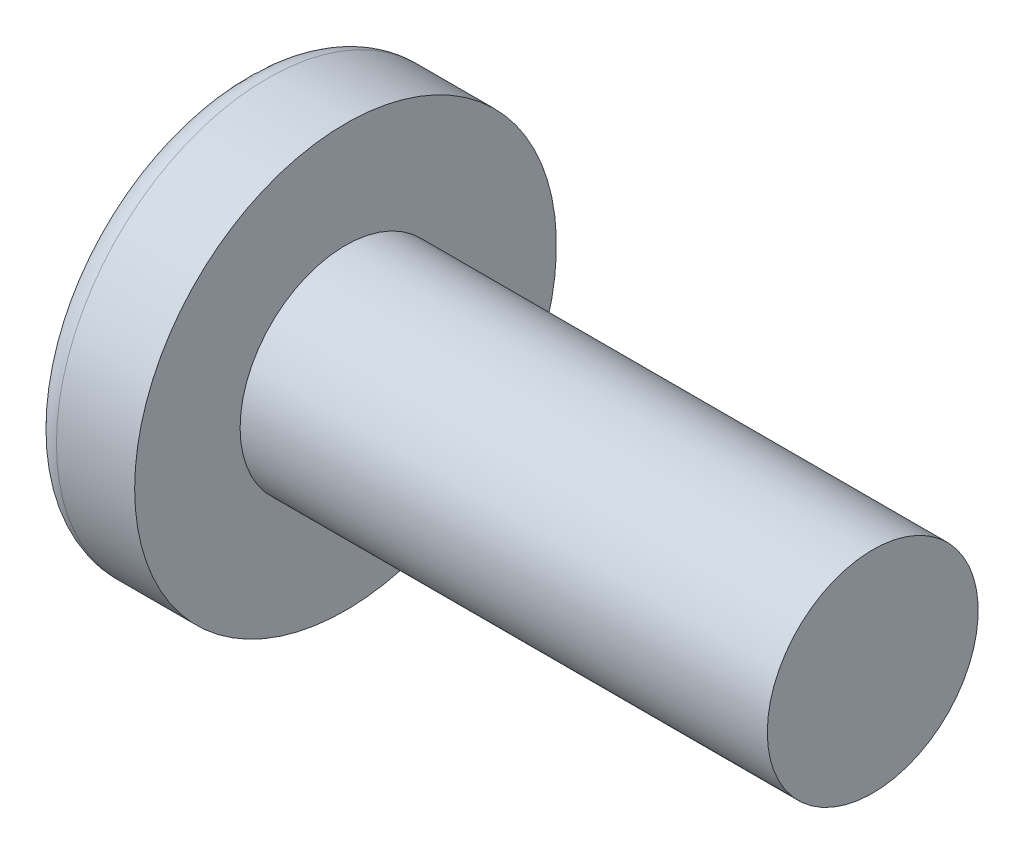
SolidWorks part; units mm, degrees
ref_plane "Plane1" through (0, 0, 0) normal (0, 0, 1) x (1, 0, 0)
ref_plane "Plane2" through (0, 0, 0) normal (0, 1, 0) x (1, 0, 0)
ref_plane "Plane3" through (0, 0, 0) normal (1, 0, 0) x (0, 0, -1)
sketch "BodySke" plane through (0, 0, 0) normal (0, 0, 1) x (1, 0, 0)
  line L0 (3.1, 2) -> (3.1, 4)
  line L1 (3.8, 6.35) -> (3.8, -3.175) construction
  line L2 (-25.4, 0) -> (127, 0) construction
  line L3 (13.1, 0) -> (0, 0)
  line L4 (3.1, 2) -> (13.1, 2)
  line L5 (13.1, 2) -> (13.1, 0)
  line L6 (1.6164, 4) -> (3.1, 4)
  line L7 (3.1, -2) -> (13.1, -2) construction
  line L8 (3.1, 6.35) -> (3.1, -3.175) construction
  arc A0 (1.227, 3.8007) -> (0, 0) centre (6.5, 0) ccw
  arc A2 (1.227, 3.8007) -> (1.6164, 4) centre (1.6164, 3.52) cw
  dimension "Head_fillet_rad" = 0.48
  dimension "Head_crown_rad" = 6.5
  dimension "Head_ht" = 3.1
  dimension "Diameter" = 4
  dimension "Length" = 10
  dimension "Head_dia" = 8
  dimension "Advance" = 0.7
  dimension "Thread_nom" = 10
revolve "Base-Revolve" add sketch "BodySke" angle 360 about L2
cosmetic thread "ThreadCosmetic" parameters "Thread_length"=9.3, "Thread_minor"=3.22
sketch "Sketch3" plane through (0, 0, 0) normal (1, 0, 0) x (0, 0, -1)
  line L0 (0.465, -2.2) -> (-0.465, -2.2)
  line L1 (0.465, -2.2) -> (0.465, 2.2)
  line L2 (-0.465, 2.2) -> (0.465, 2.2)
  line L3 (-0.465, 2.2) -> (-0.465, -2.2)
  dimension "D1" = 2.2
  dimension "Cross_dia" = 4.4
  dimension "D2" = 0.465
  dimension "Cross_width" = 0.93
ref_plane "Plane4" through (2.45, 0, 0) normal (1, 0, 0) x (0, 0, -1)
sketch "Sketch4" plane through (2.45, 0, 0) normal (1, 0, 0) x (0, 0, -1)
  line L0 (0.2325, -0.2325) -> (-0.2325, -0.2325)
  line L1 (0.2325, -0.2325) -> (0.2325, 0.2325)
  line L2 (-0.2325, 0.2325) -> (0.2325, 0.2325)
  line L3 (-0.2325, 0.2325) -> (-0.2325, -0.2325)
  dimension "D1" = 0.465
  dimension "D2" = 0.465
  dimension "D3" = 0.2325
  dimension "D4" = 0.2325
loft "Cut-Loft1" cut profiles "Sketch3", "Sketch4"
pattern_circular "CirPattern1" count 2 every 90 about axis through (0, 0, 0) along (1, 0, 0) of "Cut-Loft1"
sketch "ThdSchSke" plane through (0, 0, 0) normal (0, 0, 1) x (1, 0, 0)
  line L0 (3.8, -1.61) -> (3.5269, -2)
  line L1 (3.8, -1.61) -> (4.0731, -2)
  line L2 (4.0731, -2) -> (4.0731, -2.5)
  line L3 (-3.175, 0) -> (5.1513, 0) construction
  line L5 (4.0731, -2.5) -> (3.5269, -2.5)
  line L6 (3.5269, -2.5) -> (3.5269, -2)
  dimension "Thread_minor" = 3.22
  dimension "Diameter" = 4
  dimension "Start" = 3.8
  dimension "SideAngle" = 55
  dimension "VeeAngle" = 70
  dimension "Overcut" = 5
revolve "ThreadSchematic" [suppressed] cut sketch "ThdSchSke" angle 360 about L3
pattern_linear "ThdSchPat" [suppressed]
equation "\"D1@Sketch3\" = \"Cross_dia@Sketch3\" / 2"
equation "\"D2@Sketch3\" = \"Cross_width@Sketch3\" / 2"
equation "\"D1@Sketch4\" = \"Cross_width@Sketch3\" *.5"
equation "\"D2@Sketch4\" = \"D1@Sketch4\""
equation "\"D3@Sketch4\" = \"D1@Sketch4\" / 2"
equation "\"D4@Sketch4\" = \"D2@Sketch4\" / 2"
equation "\"Thread_length@ThreadCosmetic\" = ((sgn( (\"Length@BodySke\" - \"Advance@BodySke\" ) - \"Thread_nom@BodySke\" )-1)*( (\"Length@BodySke\" - \"Advance@BodySke\" ) - \"Thread_nom@BodySke\" ))/-2+ \"Thread_nom@BodySke\""
equation "\"Thread_minor@ThdSchSke\" = \"Thread_minor@ThreadCosmetic\""
equation "\"Diameter@ThdSchSke\" = \"Diameter@BodySke\""
equation "\"Overcut@ThdSchSke\" = \"Diameter@BodySke\" * 1.25"
equation "\"Start@ThdSchSke\" = \"Head_ht@BodySke\" + \"Length@BodySke\" - \"Thread_length@ThreadCosmetic\"  '---Non-countersunk---"
equation "\"Num_threads@ThdSchPat\" = int( \"Thread_length@ThreadCosmetic\" / \"Advance@BodySke\" + 0.999 )  + 1"
equation "\"Advance@ThdSchPat\" = \"Thread_length@ThreadCosmetic\" /  (\"Num_threads@ThdSchPat\" - 1) 'relax it"
